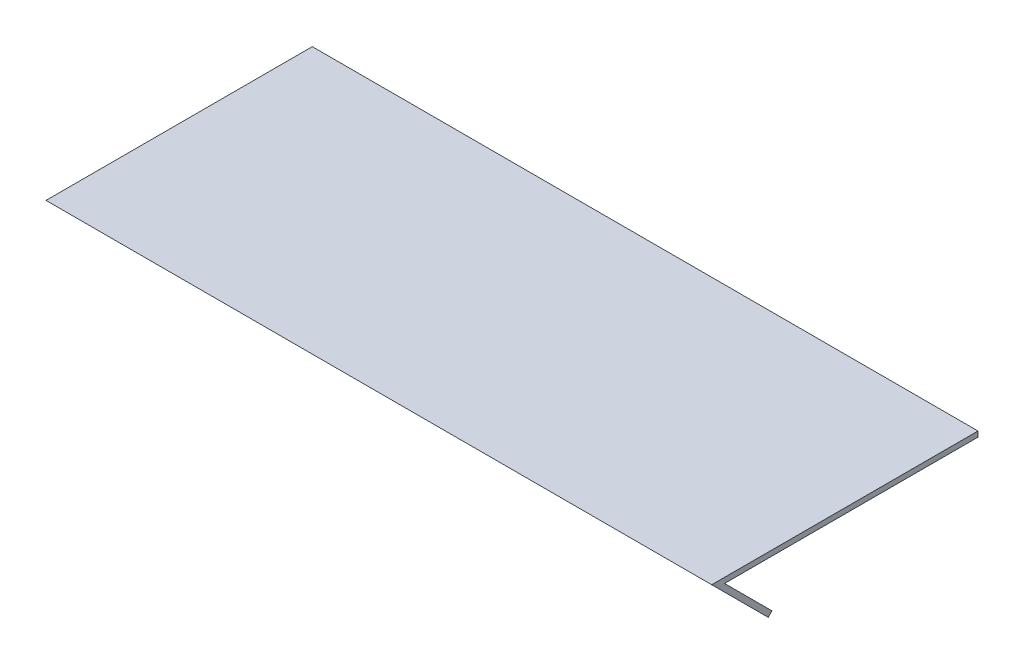
SolidWorks part; units mm, degrees
ref_plane "Plan de face" through (0, 0, 0) normal (0, 0, 1) x (1, 0, 0)
ref_plane "Plan de dessus" through (0, 0, 0) normal (0, 1, 0) x (1, 0, 0)
ref_plane "Plan de droite" through (0, 0, 0) normal (1, 0, 0) x (0, 0, -1)
sketch "Esquisse1" plane through (0, 0, 0) normal (1, 0, 0) x (0, 0, -1)
  line L0 (0, 0) -> (17.799, -17.799)
  line L1 (17.799, -17.799) -> (16.3848, -19.2132)
  line L2 (16.3848, -19.2132) -> (-4.8284, 2)
  line L3 (-4.8284, 2) -> (95.1716, 2)
  line L4 (95.1716, 2) -> (95.1716, 0)
  line L5 (95.1716, 0) -> (0, 0)
  dimension "D1" = 2
  dimension "D2" = 2
  dimension "D3" = 45
  dimension "D4" = 100
  dimension "D5" = 30
extrude "Boss.-Extru.1" add sketch "Esquisse1" along normal mid plane 250
